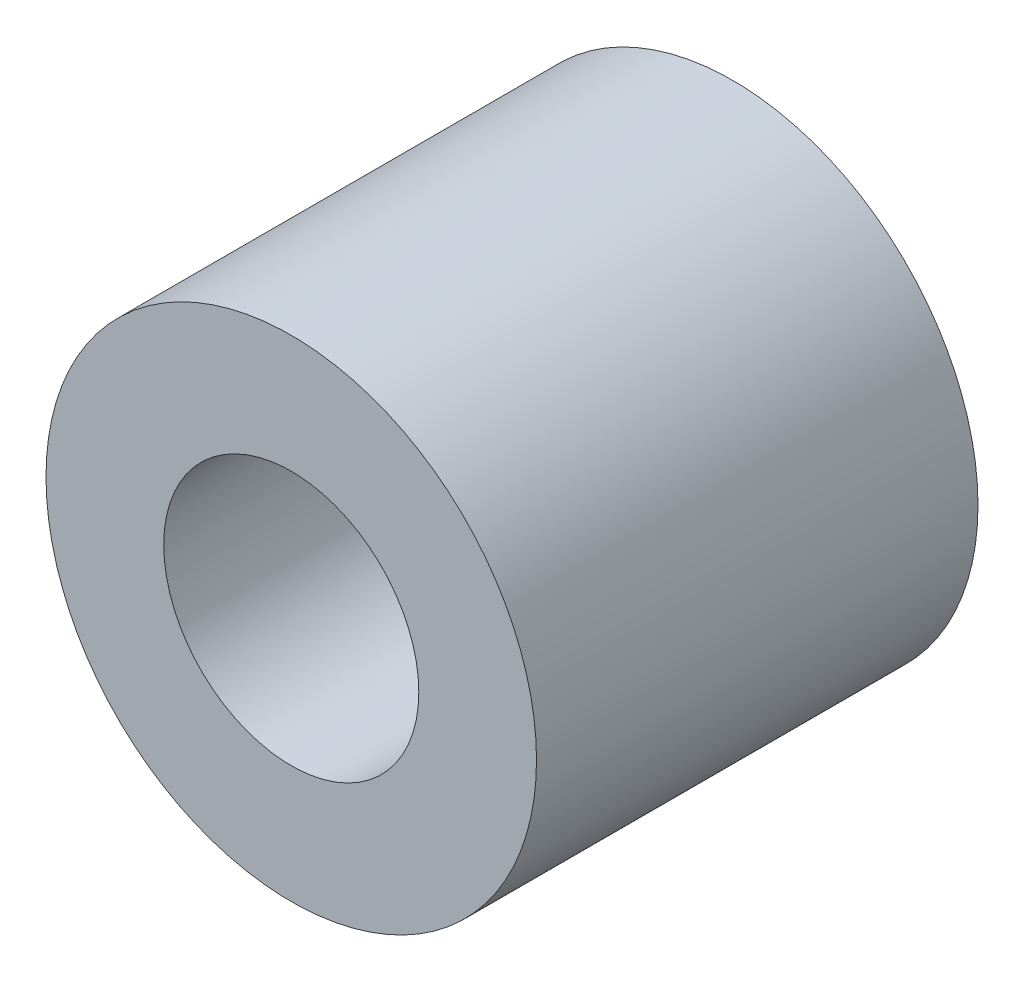
SolidWorks part; units mm, degrees
material "1060 Alloy"
ref_plane "Front Plane" through (0, 0, 0) normal (0, 0, 1) x (1, 0, 0)
ref_plane "Top Plane" through (0, 0, 0) normal (0, 1, 0) x (1, 0, 0)
ref_plane "Right Plane" through (0, 0, 0) normal (1, 0, 0) x (0, 0, -1)
sketch "Sketch1" plane through (0, 0, 0) normal (0, 0, 1) x (1, 0, 0)
  circle A0 centre (0, 0) radius 2.6
  circle A1 centre (0, 0) radius 5
  dimension "D1" = 5.2
  dimension "D2" = 10
extrude "Boss-Extrude1" add sketch "Sketch1" along normal blind 9
